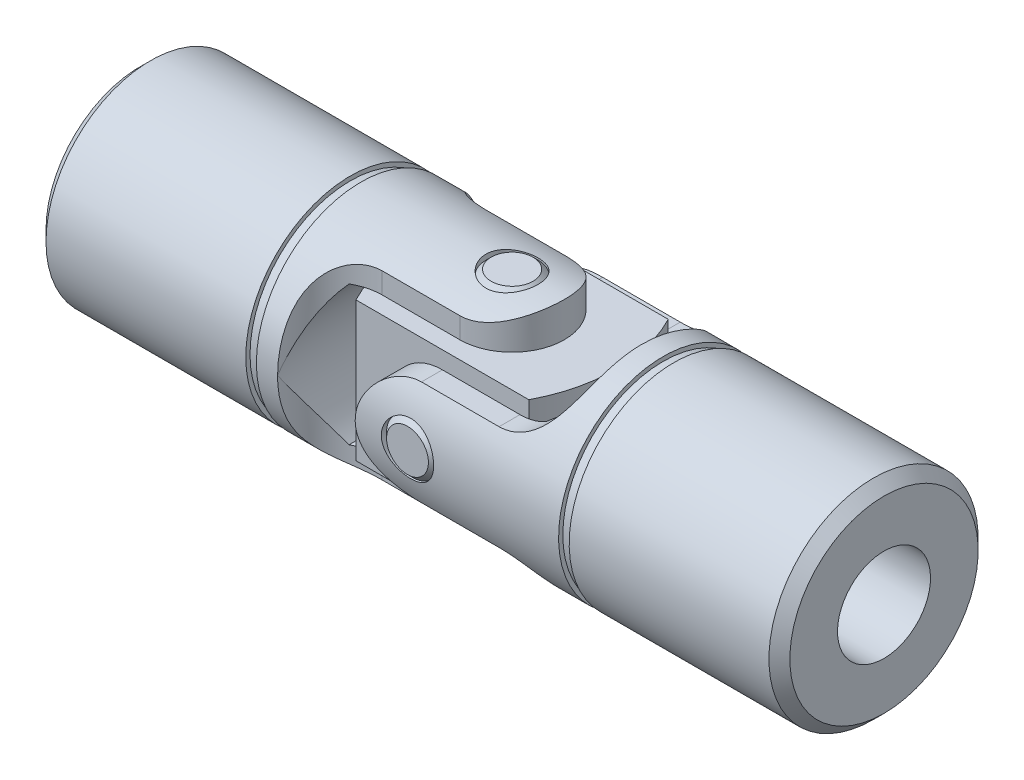
SolidWorks part; units mm, degrees
ref_plane "Front Plane" through (0, 0, 0) normal (0, 0, 1) x (1, 0, 0)
ref_plane "Top Plane" through (0, 0, 0) normal (0, 1, 0) x (1, 0, 0)
ref_plane "Right Plane" through (0, 0, 0) normal (1, 0, 0) x (0, 0, -1)
sketch "Sketch0" plane through (0, 0, 0) normal (0, 1, 0) x (1, 0, 0)
  line L0 (-25.4, 0) -> (25.4, 0) construction
  line L1 (-25.4, 7.1437) -> (-25.4, -7.1437) construction
  line L2 (-11.1125, 3.175) -> (-11.1125, -3.175) construction
  line L3 (-11.1125, 3.175) -> (-7.9375, 0) construction
  line L4 (-7.9375, 0) -> (-11.1125, -3.175) construction
  line L5 (-9.525, 1.5875) -> (-9.525, -1.5875) construction
  point P7 (-11.1125, 0)
  point P8 (0, 0)
  point P12 (-9.525, 0)
sketch "Sketch1" plane through (0, 0, 0) normal (0, 1, 0) x (1, 0, 0)
  line L0 (-25.4, 7.1437) -> (-11.043, 7.1437)
  line L1 (3.5719, 7.1438) -> (3.5719, 0)
  line L2 (3.5719, 0) -> (-25.4, 0)
  line L3 (-25.4, 0) -> (-25.4, 7.1437)
  line L4 (-25.4, 7.1437) -> (-25.4, -7.1437) construction
  line L5 (-25.4, 0) -> (25.4, 0) construction
  line L6 (-10.3187, 7.1437) -> (3.5719, 7.1438)
  line L7 (-10.3187, 1.5875) -> (-10.3187, 6.854) construction
  line L8 (-11.043, 7.1437) -> (-11.043, 6.854)
  line L9 (-11.043, 6.854) -> (-10.3187, 6.854)
  line L10 (-10.3187, 7.1437) -> (-10.3187, 6.854)
  line L11 (0, 0) -> (7.1437, 0) construction
  line L12 (-9.525, 1.5875) -> (-11.1125, 1.5875) construction
  line L13 (-11.1125, 3.175) -> (-11.1125, -3.175) construction
  circle A0 centre (0, 0) radius 7.1437 construction
  dimension "D1" = 0.7243
  dimension "D2" = 0.2897
  dimension "D3" = 28.9719
revolve "Revolve1" add sketch "Sketch1" angle 360 about L0
chamfer "Chamfer1" distance 0.7144 angle 45 1 edges at (-25.4, 0, 7.1437)
sketch "Sketch2" plane through (0, 0, 0) normal (0, 1, 0) x (1, 0, 0)
  line L0 (-10.3187, 7.1437) -> (-8.8702, 7.1437) construction
  line L1 (-10.3187, 7.1437) -> (3.5719, 7.1438) construction
  line L2 (3.5719, 7.1437) -> (-10.3187, 7.1437) construction
  line L4 (-25.4, 0) -> (3.5719, 0) construction
  line L5 (-8.8702, 7.1437) -> (7.1437, 7.1437)
  line L6 (7.1437, 7.1437) -> (7.1437, -7.1437)
  line L7 (7.1437, -7.1437) -> (-8.8702, -7.1437)
  line L8 (0, 3.5719) -> (0, 0) construction
  line L9 (0, 3.5719) -> (-5.2983, 3.5719)
  line L10 (-8.8702, 7.1437) -> (-8.8702, -7.1437) construction
  line L11 (0, -3.5719) -> (-5.2983, -3.5719)
  arc A0 (-8.8702, 7.1437) -> (-5.2983, 3.5719) centre (-5.2983, 7.1437) ccw
  arc A1 (0, -3.5719) -> (0, 3.5719) centre (0, 0) ccw
  arc A2 (-5.2983, -3.5719) -> (-8.8702, -7.1437) centre (-5.2983, -7.1437) ccw
  dimension "D1" = 7.1437
  dimension "D2" = 1.4486
extrude "Extrude1" cut sketch "Sketch2" against normal through all and the other way through all
sketch "Sketch3" plane through (0, 0, 0) normal (0, 0, 1) x (1, 0, 0)
  line L0 (-7.0842, 4.7577) -> (-8.8702, 2.9718) construction
  line L1 (-7.0842, 4.7577) -> (7.1437, 4.7577)
  line L2 (-8.8702, 2.9718) -> (-8.8702, -2.9718) construction
  line L3 (-7.0842, -4.7577) -> (7.1437, -4.7577)
  line L4 (7.1437, 4.7577) -> (7.1437, -4.7577)
  line L5 (-8.8702, -2.9718) -> (-7.0842, -4.7577) construction
  line L6 (-8.8702, 0) -> (-5.2983, 0) construction
  line L7 (-5.2983, -6.1867) -> (-5.2983, 6.1867) construction
  line L8 (7.1437, 0) -> (-8.8702, 0) construction
  line L9 (-7.0842, 0) -> (-7.0842, 4.7577) construction
  arc A0 (-7.0842, 4.7577) -> (-7.0842, -4.7577) centre (-1.6399, 0) ccw
  dimension "D1" = 9.5155
extrude "Extrude3" cut sketch "Sketch3" against normal through all and the other way through all
sketch "Sketch4" plane through (-25.4, 0, 0) normal (-1, 0, 0) x (0, 0, 1)
  circle A0 centre (0, 0) radius 3.175
extrude "Extrude4" cut sketch "Sketch4" against normal up to vertex (14.2875 mm away) up to point (-11.1125, 0, -3.175)
sketch "Sketch5" plane through (-11.1125, 0, 0) normal (-1, 0, 0) x (0, 0, 1)
  circle A0 centre (0, 0) radius 3.175 construction
  circle A1 centre (0, 0) radius 3.175
extrude "Extrude5" cut sketch "Sketch5" against normal through all draft 45
sketch "Sketch6" plane through (0, 0, 0) normal (0, 1, 0) x (1, 0, 0)
  line L0 (-25.4, 0) -> (25.4, 0) construction
  line L1 (3.5719, 0) -> (1.7859, 0) construction
  line L2 (1.7859, 0) -> (0, 0) construction
  circle A0 centre (0, 0) radius 1.7859
  arc A1 (0, -3.5719) -> (0, 3.5719) centre (0, 0) ccw construction
  dimension "D1" = 3.5719
extrude "Extrude6" cut sketch "Sketch6" against normal through all and the other way through all
mirror "Mirror1" about plane through (0, 0, 0) normal (1, 0, 0) of bodies 109 122
move or copy body "Body-Move/Copy1" bodies to move or copy 110 copy no rotation origin (0, 0, 0) rotation axis (1, 0, 0) rotation angle 90
sketch "Sketch18" plane through (0, 0, 0) normal (0, 1, 0) x (1, 0, 0)
  line L0 (-47.625, -3.175) -> (-11.1125, -3.175)
  line L3 (-47.625, 3.175) -> (-11.1125, 3.175)
  line L4 (-11.1125, 3.175) -> (-11.1125, -3.175)
  line L5 (11.1125, 3.175) -> (11.1125, -3.175)
  line L6 (11.1125, -3.175) -> (25.4, -3.175)
  line L7 (11.1125, 3.175) -> (25.4, 3.175)
  line L8 (0, 0) -> (11.1125, 0) construction
  line L9 (25.4, -6.4294) -> (25.4, 6.4294) construction
  line L11 (-11.1125, -3.175) -> (-11.1125, 3.175) construction
sketch "Sketch10" plane through (0, 0, 0) normal (0, 0, 1) x (1, 0, 0)
  line L0 (-7.0842, 4.7577) -> (7.0842, -4.7577) construction
  line L1 (-7.0842, 4.7577) -> (7.0842, 4.7577)
  line L2 (-7.0842, 4.7577) -> (-7.0842, -4.7577)
  line L3 (-7.0842, -4.7577) -> (7.0842, -4.7577)
  line L4 (7.0842, 4.7577) -> (7.0842, -4.7577)
  line L5 (0, 4.7577) -> (3.5719, 4.7577) construction
extrude "Extrude10" add sketch "Sketch10" against normal up to surface and the other way up to surface separate body
sketch "Sketch20" plane through (0, 4.7577, 0) normal (0, 1, 0) x (1, 0, 0)
  line L4 (7.0842, 4.7577) -> (-7.0842, 4.7577) construction
  line L5 (7.0842, -4.7577) -> (-7.0842, -4.7577) construction
  line L6 (-7.0842, 4.7577) -> (-7.0842, -4.7577) construction
  line L7 (7.0842, 4.7577) -> (7.0842, -4.7577) construction
  line L8 (8.1002, -5.7737) -> (8.1002, 5.7737)
  line L9 (8.1002, 5.7737) -> (-8.1002, 5.7737)
  line L10 (-8.1002, 5.7737) -> (-8.1002, -5.7737)
  line L11 (-8.1002, -5.7737) -> (8.1002, -5.7737)
  line L12 (8.1002, -5.7737) -> (8.1002, 5.7737)
  line L13 (8.1002, 5.7737) -> (5.9035, 5.7737)
  line L14 (-8.1002, 5.7737) -> (-8.1002, -5.7737)
  line L15 (-8.1002, -5.7737) -> (-5.9035, -5.7737)
  line L16 (-5.9035, 4.7577) -> (-5.9035, 5.7737)
  line L17 (5.9035, 4.7577) -> (5.9035, 5.7737)
  line L18 (5.9035, -4.7577) -> (5.9035, -5.7737)
  line L19 (-5.9035, -4.7577) -> (-5.9035, -5.7737)
  line L20 (-5.9035, 5.7737) -> (-8.1002, 5.7737)
  line L21 (5.9035, -5.7737) -> (8.1002, -5.7737)
  line L22 (-25.4, 0) -> (3.5719, 0) construction
  line L23 (7.0842, 4.7577) -> (-7.0842, 4.7577) construction
  arc A0 (5.9035, 4.7577) -> (5.9035, -4.7577) centre (-3.092, 0) cw
  arc A1 (-5.9035, 4.7577) -> (-5.9035, -4.7577) centre (3.092, 0) ccw
  dimension "D2" = 14.1684
  dimension "D3" = 1.1807
extrude "Cut-Extrude2" cut sketch "Sketch20" against normal through all
sketch "Sketch13" plane through (0, 0, 0) normal (0, 1, 0) x (1, 0, 0)
  circle A0 centre (0, 0) radius 1.7859 construction
  circle A1 centre (0, 0) radius 1.7859
extrude "Extrude13" cut sketch "Sketch13" against normal through all and the other way through all
sketch "Sketch14" plane through (0, 0, 0) normal (0, 1, 0) x (1, 0, 0)
  circle A1 centre (0, 0) radius 1.7859
  circle A2 centre (0, 0) radius 1.7859
  dimension "D1" = 0
extrude "Extrude14" add sketch "Sketch14" along normal mid plane 14.2875 separate body
sketch "Sketch15" plane through (0, 0, 0) normal (0, 0, 1) x (1, 0, 0)
  circle A0 centre (0, 0) radius 1.7859 construction
  circle A1 centre (0, 0) radius 1.7859
extrude "Extrude15" cut sketch "Sketch15" against normal through all and the other way through all
sketch "Sketch16" plane through (0, 0, 0) normal (0, 0, 1) x (1, 0, 0)
  circle A1 centre (0, 0) radius 1.7859
  circle A2 centre (0, 0) radius 1.7859
  dimension "D1" = 0
extrude "Extrude16" add sketch "Sketch16" along normal mid plane 14.2875
chamfer "Chamfer3" distance 0.3572 angle 45 4 edges at (0, -7.1437, 1.7859) (0, 7.1437, 1.7859) (1.7859, 0, 7.1437) (1.7859, 0, -7.1437)
move or copy body "Body-Move/Copy2" [suppressed] bodies to move or copy 111 copy no rotation origin (0, 0, 0) rotation axis (0, 0, -1) rotation angle 15
equation "\"D2@Sketch3\" = \"D1@Sketch3\" / 4"
equation "\"D1@Extrude14\" = \"OD@Sketch0\""
equation "\"D1@Extrude16\" = \"D1@Extrude14\""
equation "\"D1@Sketch3\" = \"OD@Sketch0\"*.666"
equation "\"D1@Sketch1\" = \"D3@Sketch1\"*.025"
equation "\"D2@Sketch1\" = \"D1@Sketch1\"/2.5"
equation "\"D1@Chamfer1\" = \"OD@Sketch0\"/20"
equation "\"D1@Chamfer3\" = \"D1@Chamfer1\"*.50"
equation "\"D2@Sketch2\" = \"D1@Sketch1\"*2"
equation "\"D3@Sketch20\" = \"D2@Sketch20\"/12"
